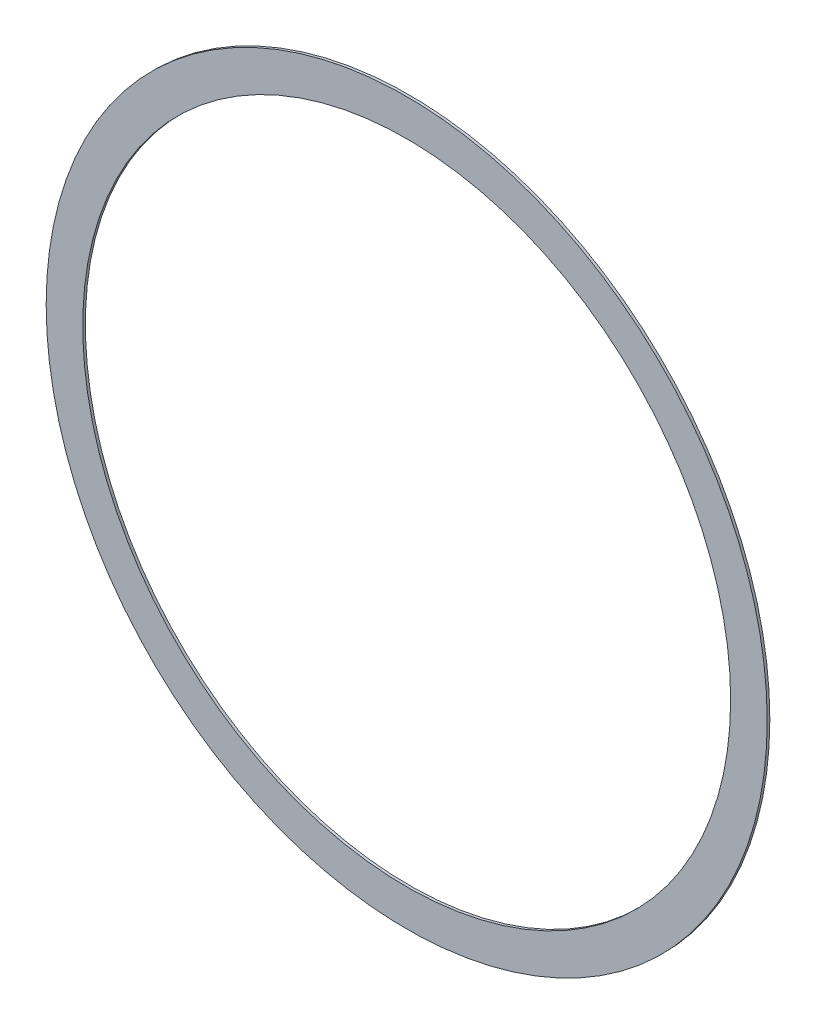
SolidWorks part; units mm, degrees
material "M/S SHIM"
ref_plane "Front Plane" through (0, 0, 0) normal (0, 0, 1) x (1, 0, 0)
ref_plane "Top Plane" through (0, 0, 0) normal (0, 1, 0) x (1, 0, 0)
ref_plane "Right Plane" through (0, 0, 0) normal (1, 0, 0) x (0, 0, -1)
sketch "Sketch1" plane through (0, 0, 0) normal (0, 0, 1) x (1, 0, 0)
  circle A0 centre (0, 0) radius 69
  circle A1 centre (0, 0) radius 62
  dimension "D1" = 138
  dimension "D2" = 124
extrude "Boss-Extrude1" add sketch "Sketch1" along normal blind 0.5
